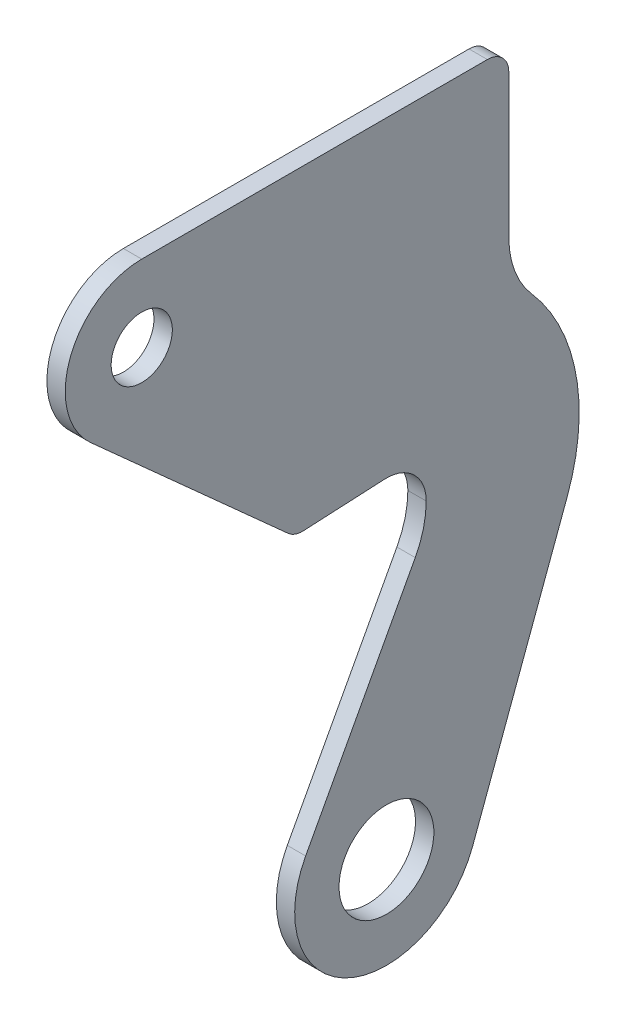
SolidWorks part; units mm, degrees
material "6061-T6 (SS)"
ref_plane "Front Plane" through (0, 0, 0) normal (0, 0, 1) x (1, 0, 0)
ref_plane "Top Plane" through (0, 0, 0) normal (0, 1, 0) x (1, 0, 0)
ref_plane "Right Plane" through (0, 0, 0) normal (1, 0, 0) x (0, 0, -1)
sketch "Sketch1" plane through (0, 0, 0) normal (1, 0, 0) x (0, 0, -1)
  line L0 (38.7866, 46.99) -> (10.16, 46.99) construction
  line L1 (-0.1667, 27.4278) -> (-7.62, 27.051)
  line L2 (2.3915, 20.518) -> (-6.7095, 3.612)
  line L3 (-7.62, 27.051) -> (-24.5627, 42.2654)
  line L4 (-20.32, 53.34) -> (10.16, 53.34)
  line L5 (10.16, 53.34) -> (10.16, 36.4928)
  line L6 (15.0055, 18.5714) -> (7.1455, -2.6469)
  circle A0 centre (0, 0) radius 3.937
  arc A1 (-6.7095, 3.612) -> (7.1455, -2.6469) centre (0, 0) ccw
  arc A2 (3.302, 24.13) -> (-0.1667, 27.4278) centre (0, 24.13) ccw
  arc A3 (3.302, 24.13) -> (2.3915, 20.518) centre (-4.318, 24.13) cw
  arc A4 (10.16, 36.4928) -> (15.0055, 18.5714) centre (0, 24.13) cw
  circle A5 centre (-20.32, 46.99) radius 2.54
  arc A6 (-24.5627, 42.2654) -> (-20.32, 53.34) centre (-20.32, 46.99) cw
  dimension "D1" = 7.874
  dimension "D2" = 6.604
  dimension "D6" = 7.62
  dimension "D7" = 0.381
  dimension "D9" = 7.62
  dimension "D11" = 12.7
  dimension "D12" = 6.35
  dimension "D14" = 5.08
  dimension "D3" = 24.13
  dimension "D4" = 10.16
  dimension "D5" = 46.99
  dimension "D8" = 7.62
  dimension "D10" = 6.35
  dimension "D13" = 30.48
extrude "Boss-Extrude1" add sketch "Sketch1" along normal mid plane 1.524
fillet "Fillet1" radius 1.778 2 edges at (0, 53.34, -10.16) (0, 27.051, 7.62)
fillet "Fillet2" radius 7.62 1 edges at (0, 36.4928, -10.16)
